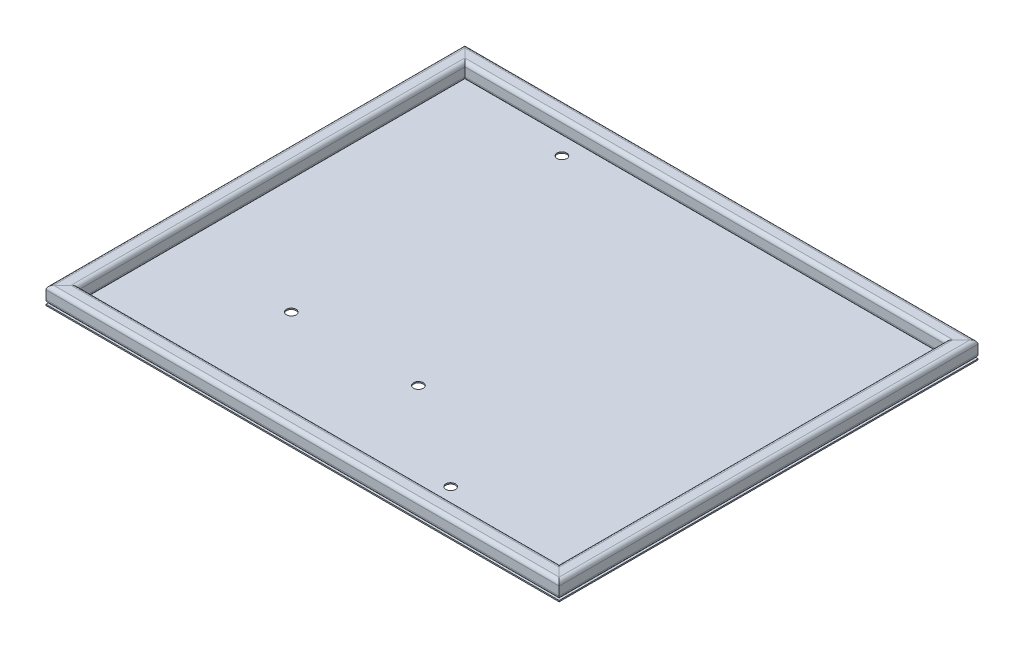
SolidWorks part; units mm, degrees
ref_plane "Alzado" through (0, 0, 0) normal (0, 0, 1) x (1, 0, 0)
ref_plane "Planta" through (0, 0, 0) normal (0, 1, 0) x (1, 0, 0)
ref_plane "Vista lateral" through (0, 0, 0) normal (1, 0, 0) x (0, 0, -1)
sketch "Croquis1" plane through (0, 0, 0) normal (0, 1, 0) x (1, 0, 0)
  line L1 (-398.2, 325) -> (398.2, 325)
  line L2 (-398.2, 325) -> (-398.2, -325)
  line L3 (-398.2, -325) -> (398.2, -325)
  line L4 (398.2, 325) -> (398.2, -325)
  line L5 (-398.2, 325) -> (398.2, -325) construction
  line L6 (-398.2, -325) -> (398.2, 325) construction
  point P0 (0, 0)
  dimension "D1" = 650
  dimension "D2" = 796.4
other "Tubo cuadrado 2 X 2 X 0.25(1)"
ref_plane "Plano1" through (-385.5, 12.7, -325) normal (0, 0, 1) x (1, 0, 0)
sketch "Sketch1" plane through (-385.5, 12.7, -325) normal (0, 0, 1) x (1, 0, 0)
  line L0 (-6.7, -9.7) -> (6.7, -9.7)
  line L1 (-9.7, -6.7) -> (-9.7, 6.7)
  line L2 (6.7, 9.7) -> (-6.7, 9.7)
  line L3 (9.7, 6.7) -> (9.7, -6.7)
  line L4 (-6.7, -12.7) -> (6.7, -12.7)
  line L5 (-12.7, -6.7) -> (-12.7, 6.7)
  line L6 (6.7, 12.7) -> (-6.7, 12.7)
  line L7 (12.7, 6.7) -> (12.7, -6.7)
  line L8 (0, 0) -> (9.7, 0) construction
  line L9 (0, 0) -> (0, 9.7) construction
  arc A0 (12.7, 6.7) -> (6.7, 12.7) centre (6.7, 6.7) ccw
  arc A1 (6.7, -12.7) -> (12.7, -6.7) centre (6.7, -6.7) ccw
  arc A2 (-12.7, -6.7) -> (-6.7, -12.7) centre (-6.7, -6.7) ccw
  arc A3 (-6.7, 12.7) -> (-12.7, 6.7) centre (-6.7, 6.7) ccw
  arc A4 (-6.7, 9.7) -> (-9.7, 6.7) centre (-6.7, 6.7) ccw
  arc A5 (9.7, 6.7) -> (6.7, 9.7) centre (6.7, 6.7) ccw
  arc A6 (6.7, -9.7) -> (9.7, -6.7) centre (6.7, -6.7) ccw
  arc A7 (-9.7, -6.7) -> (-6.7, -9.7) centre (-6.7, -6.7) ccw
  point P3 (0, 12.7)
  point P4 (12.7, 0)
  point P5 (0, -12.7)
  point P6 (-12.7, 0)
  point P7 (-12.7, 12.7)
  point P8 (-12.7, -12.7)
  point P33 (0, 0)
  point P35 (12.7, -12.7)
  point P36 (12.7, 12.7)
  point P37 (0, 0)
  dimension "D1" = 6
  dimension "Thickness" = 3
  dimension "V_leg" = 25.4
sketch "Croquis3" plane through (0, 0, 0) normal (0, -1, 0) x (1, 0, 0)
  line L1 (398.2, 325) -> (-398.2, 325)
  line L2 (398.2, 325) -> (398.2, -325)
  line L3 (398.2, -325) -> (-398.2, -325)
  line L4 (-398.2, 325) -> (-398.2, -325)
  line L5 (398.2, 325) -> (-398.2, -325) construction
  line L6 (398.2, -325) -> (-398.2, 325) construction
  point P0 (0, 0)
extrude "Saliente-Extruir1" add sketch "Croquis3" along normal blind 1.9 separate body
ref_plane "Plano2" through (0, 0, 250) normal (0, 0, 1) x (1, 0, 0)
sketch "Croquis7" plane through (0, -1.9, 0) normal (0, -1, 0) x (1, 0, 0)
  line L0 (0, 0) -> (398.2, 0) construction
  line L1 (398.2, -325) -> (398.2, 325) construction
  line L2 (0, 0) -> (0, 325) construction
  line L3 (398.2, 325) -> (-398.2, 325) construction
  line L4 (0, 325) -> (0, 145.21) construction
  line L5 (0, 145.21) -> (-197.3, 145.21) construction
  line L6 (0, 145.21) -> (0, 256.21) construction
  line L7 (0, 256.21) -> (161, 256.21) construction
  line L8 (-197.3, 145.21) -> (-197.3, -274.79) construction
  circle A0 centre (0, 145.21) radius 7.5
  circle A1 centre (161, 256.21) radius 7.5
  circle A2 centre (-197.3, 145.21) radius 7.5
  circle A3 centre (-197.3, -274.79) radius 7.5
  dimension "D6" = 15
  dimension "D7" = 15
  dimension "D8" = 15
  dimension "D9" = 15
  dimension "D1" = 179.79
  dimension "D2" = 197.3
  dimension "D3" = 111
  dimension "D4" = 161
  dimension "D5" = 420
extrude "Cortar-Extruir1" cut sketch "Croquis7" against normal blind 10
